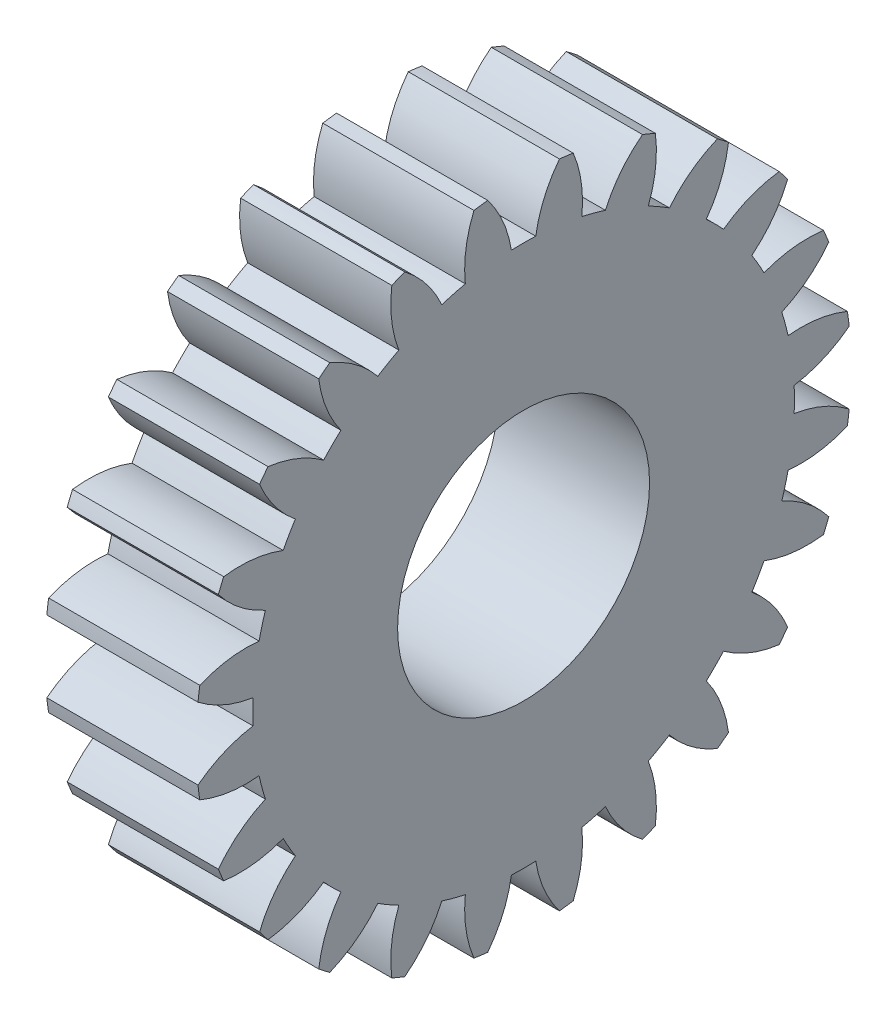
SolidWorks part; units mm, degrees
ref_plane "Plane1" through (0, 0, 0) normal (0, 0, 1) x (1, 0, 0)
ref_plane "Plane2" through (0, 0, 0) normal (0, 1, 0) x (1, 0, 0)
ref_plane "Plane3" through (0, 0, 0) normal (1, 0, 0) x (0, 0, -1)
sketch "HoldingSke" plane through (0, 0, 0) normal (0, 1, 0) x (1, 0, 0)
  line L0 (0, 0) -> (0.9135, -0.4067)
  line L1 (-15, 0) -> (100, 0) construction
  line L2 (0, 0) -> (-2.1039, 2.3779)
  line L3 (0, 0) -> (-11.863, 4.5341)
  line L4 (0, 0) -> (7.8894, 3.5126)
  line L5 (0, 0) -> (-46.8476, -17.4728)
  line L6 (0, 0) -> (-4.9738, -3.3558)
  line L7 (-2.1039, 2.3779) -> (8.6586, 51.2059)
  line L8 (-76.2, 54.61) -> (-74.4, 54.61)
  line L9 (-71.009, 38.7566) -> (-53.1078, 45.2721)
  line L10 (-76.2, 71.12) -> (104.1128, 71.12)
  line L11 (0, 0) -> (-6, 0)
  line L12 (-76.2, 101.6) -> (-76.162, 101.6)
  line L13 (24.9733, 27.94) -> (52.9518, 28.4284)
  line L14 (24.9733, 27.94) -> (24.9743, 27.94)
  line L15 (24.9733, 27.94) -> (100.4006, 29.5858)
  line L16 (-63.627, -1) -> (-12.827, -1)
  circle A0 centre (0, 0) radius 5
  circle A1 centre (0, 0) radius 10.749
  circle A2 centre (0, 0) radius 37.5
  circle A3 centre (0, 0) radius 5
  dimension "MHD" = 21.498
  dimension "Hub_dia" = 75
  dimension "Bore" = 10
  dimension "MBD" = 10
  dimension "Num_teeth" = 24
  dimension "Pitch" = 1
  dimension "Overall_len" = 50
  dimension "Show_teeth" = 24
  dimension "Thickness" = 6
  dimension "OAL" = 50.0001
  dimension "T_dim" = 1.8
  dimension "Ap" = 20
  dimension "H" = 19.05
  dimension "Pitch_radius" = 180.3128
  dimension "Width" = 6
  dimension "Backlash" = 0.038
  dimension "Addendum_fac" = 1
  dimension "Dedendum_fac" = 1.25
  dimension "Clearance_fac" = 0.25
  dimension "Dedendum_add" = 0.001
  dimension "Module" = 1
sketch "BasProSke" plane through (0, 0, 0) normal (0, 1, 0) x (1, 0, 0)
  line L0 (-10, 0) -> (60, 0) construction
  line L1 (0, 0) -> (0, 13)
  line L2 (0, 0) -> (6, 0)
  line L3 (6, 0) -> (6, 13)
  line L4 (6, 13) -> (0, 13)
  dimension "Thickness" = 6
  dimension "Diameter" = 26
revolve "Base-Revolve" add sketch "BasProSke" angle 360 about L0
sketch "TooCutSke" plane through (0, 0, 0) normal (1, 0, 0) x (0, 0, -1)
  line L1 (0, 0) -> (0, 107) construction
  line L2 (0, 0) -> (-0.8513, 11.9698) construction
  line L3 (0, 0) -> (-3.127, 23.752) construction
  line L4 (-0.8513, 11.9698) -> (-1.5635, 11.876) construction
  arc A0 (0.4834, 10.7381) -> (-0.4834, 10.7381) centre (0, 0) ccw
  arc A1 (1.4409, 12.9455) -> (-1.4409, 12.9455) centre (0, 0) ccw
  circle A2 centre (0, 0) radius 12 construction
  circle A3 centre (0, 0) radius 11.2763 construction
  arc A4 (-0.4834, 10.7381) -> (-1.4409, 12.9455) centre (-5.2252, 9.9926) ccw
  arc A5 (1.4409, 12.9455) -> (0.4834, 10.7381) centre (5.2252, 9.9926) ccw
  dimension "Root_dia" = 21.498
  dimension "Overcut_dia" = 26.0508
  dimension "Pitch_dia" = 24
  dimension "Base_dia" = 22.5526
  dimension "Flank_rad" = 4.8
  dimension "Half_ang" = 7.5
  dimension "Half_CT" = 0.7183
extrude "ToothCut" cut sketch "TooCutSke" along normal through all
fillet "Breaks" [suppressed] radius 0.02
fillet "RootFillets" [suppressed] radius 0.251
pattern_circular "TeethCuts" count 24 every 15 about axis through (-10, 0, 0) along (1, 0, 0) of "ToothCut", "RootFillets", "Breaks"
sketch "HubNeaOneSke" plane through (0, 0, 0) normal (-1, 0, 0) x (0, 0, 1)
  circle A0 centre (0, 0) radius 10.749
  dimension "Diameter" = 21.498
extrude "HubNearOne" [suppressed] add sketch "HubNeaOneSke" along normal blind 44.0001
sketch "HubNeaBotSke" plane through (0, 0, 0) normal (-1, 0, 0) x (0, 0, 1)
  circle A0 centre (0, 0) radius 10.749
  dimension "Diameter" = 21.498
extrude "HubNearBoth" [suppressed] add sketch "HubNeaBotSke" along normal blind 22
ref_plane "FarPln" through (6, 0, 0) normal (1, 0, 0) x (0, 0, -1)
sketch "HubFarSke" plane through (6, 0, 0) normal (1, 0, 0) x (0, 0, -1)
  circle A0 centre (0, 0) radius 10.749
  dimension "Diameter" = 21.498
extrude "HubFar" [suppressed] add sketch "HubFarSke" along normal blind 22
sketch "BorSke" plane through (0, 0, 0) normal (1, 0, 0) x (0, 0, -1)
  circle A0 centre (0, 0) radius 5
  dimension "Diameter" = 10
extrude "Bore" cut sketch "BorSke" along normal mid plane 100.0001
sketch "KeySke" plane through (0, 0, 0) normal (1, 0, 0) x (0, 0, -1)
  line L0 (-1.5, 0) -> (-1.5, 6.8)
  line L1 (-1.5, 6.8) -> (1.5, 6.8)
  line L2 (1.5, 6.8) -> (1.5, 0)
  line L3 (0, 0) -> (0, 34) construction
  line L4 (-1.5, 0) -> (1.5, 0)
  dimension "Offset" = 6.8
  dimension "Width" = 3
extrude "Keyway" [suppressed] cut sketch "KeySke" along normal mid plane 100.0001
pattern_circular "Keyway2" [suppressed] count 2 every 90 about axis through (-10, 0, 0) along (1, 0, 0)
equation "' \"Module@HoldingSke\" = 6.35"
equation "' \"Num_teeth@HoldingSke\" = 12"
equation "' \"Ap@HoldingSke\" =  20"
equation "' \"Ap@HoldingSke\" = 20"
equation "' \"Width@HoldingSke\" = 0.5 * 25.4"
equation "' \"Hub_dia@HoldingSke\"= 1 * 25.4"
equation "' \"Hub_dia@HoldingSke\" = 1 * 25.4"
equation "' \"Overall_len@HoldingSke\" = 1.0 * 25.4"
equation "' \"Bore@HoldingSke\" = 0.75 * 25.4"
equation "' \"T_dim@HoldingSke\" = 0.1 * 25.4"
equation "' \"Width@KeySke\" = 0.25 * 25.4"
equation "' \"Show_teeth@HoldingSke\" = 13"
equation "' \"Backlash@HoldingSke\" = 0.009 * 25.4"
equation "' \"Addendum_fac@HoldingSke\" = 1.0"
equation "' \"Dedendum_fac@HoldingSke\" = 1.25"
equation "' \"Dedendum_add@HoldingSke\" = 0.00005 * 25.4"
equation "' \"Clearance_fac@HoldingSke\" = 0.25"
equation "\"Pitch@HoldingSke\" = 1 / \"Module@HoldingSke\""
equation "\"Overcut_dia@TooCutSke\" = (\"Num_teeth@HoldingSke\" + 2 * \"Addendum_fac@HoldingSke\") / \"Pitch@HoldingSke\" + 0.002 * 25.4"
equation "\"Pitch_dia@TooCutSke\" = \"Num_teeth@HoldingSke\" / \"Pitch@HoldingSke\""
equation "\"Base_dia@TooCutSke\" = \"Num_teeth@HoldingSke\" / \"Pitch@HoldingSke\" * cos((\"Ap@HoldingSke\"  * 3.14159265 / 180))"
equation "\"Root_dia@TooCutSke\" = (\"Num_teeth@HoldingSke\" + 2) / \"Pitch@HoldingSke\" - 2 * (\"Addendum_fac@HoldingSke\" + \"Dedendum_fac@HoldingSke\") / \"Pitch@HoldingSke\" - \"Dedendum_add@HoldingSke\" * 2"
equation "\"Half_ang@TooCutSke\" = 180 / \"Num_teeth@HoldingSke\""
equation "\"Half_CT@TooCutSke\" = \"Num_teeth@HoldingSke\" / \"Pitch@HoldingSke\" * sin((3.14159265 / 2 / \"Num_teeth@HoldingSke\")) / 2 - 7 * \"Backlash@HoldingSke\" / 4"
equation "\"Flank_rad@TooCutSke\" = \"Num_teeth@HoldingSke\" / \"Pitch@HoldingSke\" / 5"
equation "\"Radius@RootFillets\" = \"Clearance_fac@HoldingSke\" / \"Pitch@HoldingSke\" + \"Dedendum_add@HoldingSke\""
equation "\"Break_rad@Breaks\" = 0.02 / \"Pitch@HoldingSke\""
equation "\"Thickness@HoldingSke\" = \"Width@HoldingSke\""
equation "\"OAL@HoldingSke\" = \"Thickness@HoldingSke\""
equation "\"MHD@HoldingSke\" = (\"Num_teeth@HoldingSke\" + 2) / \"Pitch@HoldingSke\" - 2 * (\"Addendum_fac@HoldingSke\" + \"Dedendum_fac@HoldingSke\")  / \"Pitch@HoldingSke\" - \"Dedendum_add@HoldingSke\" * 2"
equation "\"MBD@HoldingSke\" = (\"Num_teeth@HoldingSke\" + 2) / \"Pitch@HoldingSke\" - 2 * (\"Addendum_fac@HoldingSke\" + \"Dedendum_fac@HoldingSke\")  / \"Pitch@HoldingSke\" - \"Dedendum_add@HoldingSke\" * 2 - 0.002 * 25.4"
equation "\"MHD@HoldingSke\" = ((sgn( \"MHD@HoldingSke\" - \"Hub_dia@HoldingSke\" )-1)*( \"MHD@HoldingSke\" - \"Hub_dia@HoldingSke\" ))/-2+ \"Hub_dia@HoldingSke\""
equation "\"MBD@HoldingSke\" = ((sgn( \"MBD@HoldingSke\" - \"Bore@HoldingSke\" )-1)*( \"MBD@HoldingSke\" - \"Bore@HoldingSke\" ))/-2+ \"Bore@HoldingSke\""
equation "\"OAL@HoldingSke\" = ((sgn( \"OAL@HoldingSke\" - \"Overall_len@HoldingSke\" )+1)*( \"OAL@HoldingSke\" - \"Overall_len@HoldingSke\" ))/2 + \"Overall_len@HoldingSke\" + 0.000002 * 25.4"
equation "\"Num_teeth@TeethCuts\" = int( \"Show_teeth@HoldingSke\" ) + 1"
equation "\"Num_teeth@TeethCuts\" = ((sgn( \"Num_teeth@TeethCuts\" - \"Num_teeth@HoldingSke\" )-1)*( \"Num_teeth@TeethCuts\" - \"Num_teeth@HoldingSke\" ))/-2+ \"Num_teeth@HoldingSke\""
equation "\"Num_teeth@TeethCuts\" = ((sgn( \"Num_teeth@TeethCuts\" - 2.0)+1)*( \"Num_teeth@TeethCuts\" - 2.0))/2 +2.0"
equation "\"Angle@TeethCuts\" = 360.0 / \"Num_teeth@HoldingSke\""
equation "\"Diameter@BasProSke\" = (\"Num_teeth@HoldingSke\" + 2 * \"Addendum_fac@HoldingSke\") / \"Pitch@HoldingSke\""
equation "\"Thickness@BasProSke\"  = \"Thickness@HoldingSke\""
equation "' \"Fillet_rad@BasProSke\" =  \"Thickness@HoldingSke\" * 0.05"
equation "' \"Fillet_rad@BasProSke\" = \"Thickness@HoldingSke\" * 0.05"
equation "\"MHD@HoldingSke\" = ((sgn( \"MHD@HoldingSke\" - \"Root_dia@TooCutSke\" )-1)*( \"MHD@HoldingSke\" - \"Root_dia@TooCutSke\" ))/-2+ \"Root_dia@TooCutSke\""
equation "\"Diameter@HubNeaOneSke\" = \"MHD@HoldingSke\""
equation "\"Length@HubNearOne\" = \"OAL@HoldingSke\" - \"Thickness@BasProSke\""
equation "\"Diameter@HubNeaBotSke\" = \"MHD@HoldingSke\""
equation "\"Length@HubNearBoth\" = ( \"OAL@HoldingSke\" - \"Thickness@BasProSke\" ) / 2.0"
equation "\"Thickness@FarPln\" = \"Thickness@BasProSke\""
equation "\"Diameter@HubFarSke\" = \"MHD@HoldingSke\""
equation "\"Length@HubFar\" = ( \"OAL@HoldingSke\" - \"Thickness@BasProSke\" ) / 2.0"
equation "\"Diameter@BorSke\" = \"MBD@HoldingSke\""
equation "\"D1@Bore\" = \"OAL@HoldingSke\" * 2.0"
equation "\"D1@Keyway\" = \"OAL@HoldingSke\" * 2.0"
equation "\"Offset@KeySke\" = \"T_dim@HoldingSke\" + \"MBD@HoldingSke\" / 2.0"
